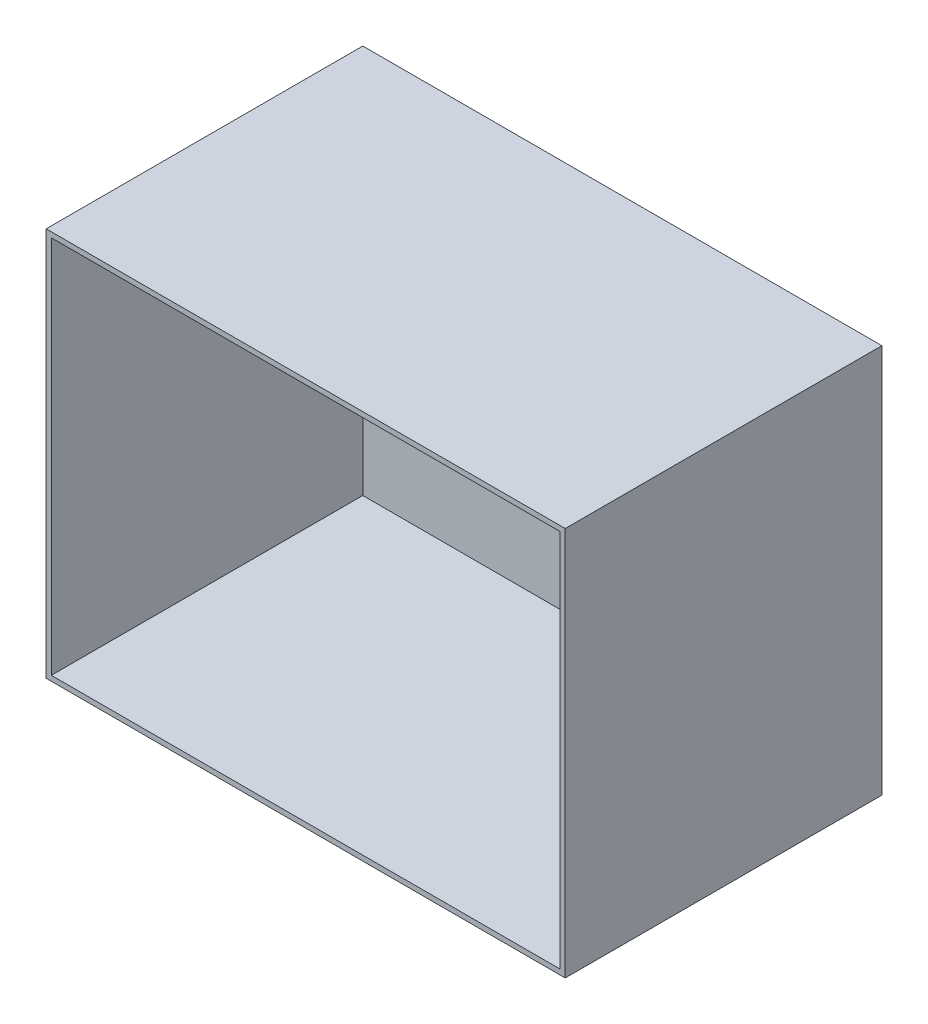
SolidWorks part; units mm, degrees
ref_plane "Front Plane" through (0, 0, 0) normal (0, 0, 1) x (1, 0, 0)
ref_plane "Top Plane" through (0, 0, 0) normal (0, 1, 0) x (1, 0, 0)
ref_plane "Right Plane" through (0, 0, 0) normal (1, 0, 0) x (0, 0, -1)
sketch "Sketch1" plane through (0, 0, 0) normal (0, 0, 1) x (1, 0, 0)
  line L1 (0, 0) -> (100, 0)
  line L2 (0, 0) -> (0, 75)
  line L3 (0, 75) -> (100, 75)
  line L4 (100, 0) -> (100, 75)
  dimension "D1" = 75
  dimension "D2" = 100
extrude "Boss-Extrude1" add sketch "Sketch1" along normal blind 1
sketch "Sketch2" plane through (0, 0, 1) normal (0, 0, 1) x (1, 0, 0)
  line L0 (100, 0) -> (100, 75) construction
  line L1 (0, 75) -> (100, 75)
  line L2 (0, 75) -> (0, 74)
  line L3 (0, 74) -> (100, 74)
  line L4 (100, 75) -> (100, 74)
  line L5 (0, 0) -> (100, 0) construction
  line L6 (100, 74) -> (99, 74)
  line L7 (100, 74) -> (100, 0)
  line L8 (100, 0) -> (99, 0)
  line L9 (99, 74) -> (99, 0)
  line L10 (0, 75) -> (0, 0) construction
  line L11 (99, 0) -> (0, 0)
  line L12 (99, 0) -> (99, 1)
  line L13 (99, 1) -> (0, 1)
  line L14 (0, 0) -> (0, 1)
  line L16 (0, 1) -> (1, 1)
  line L17 (0, 1) -> (0, 74)
  line L18 (0, 74) -> (1, 74)
  line L19 (1, 1) -> (1, 74)
  line M4 (0, 75) -> (0, 0)
  line M5 (0, 0) -> (100, 0)
  line M6 (100, 0) -> (100, 75)
  line M7 (100, 75) -> (0, 75)
  dimension "D1" = 1
  dimension "D2" = 1
  dimension "D3" = 1
  dimension "D4" = 1
extrude "Boss-Extrude2" add sketch "Sketch2" along normal blind 60 contours L3 M4 M6 M7 | L13 L19 L3 M4 | L9 L13 M4 M5 | L3 L9 M5 M6
